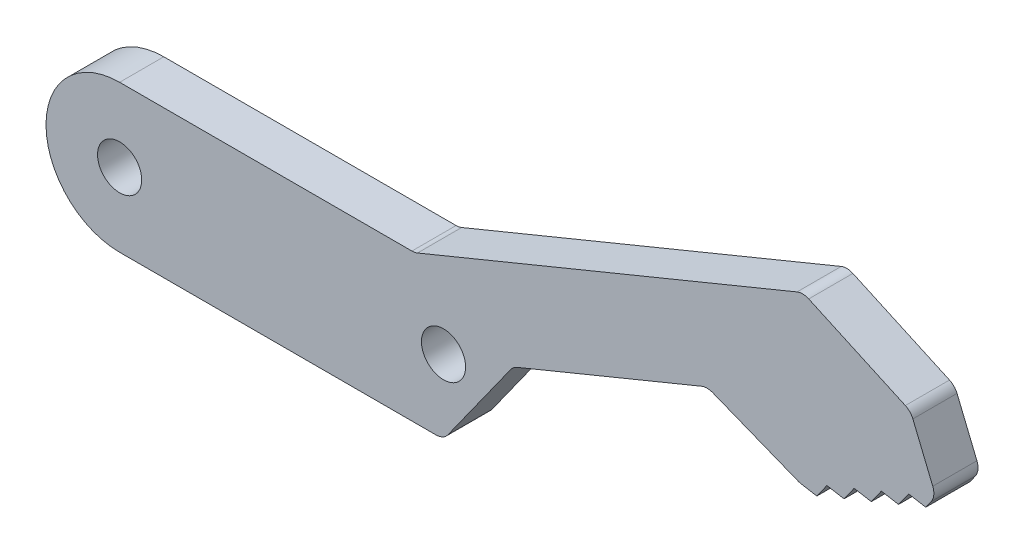
SolidWorks part; units mm, degrees
ref_plane "Front Plane" through (0, 0, 0) normal (0, 0, 1) x (1, 0, 0)
ref_plane "Top Plane" through (0, 0, 0) normal (0, 1, 0) x (1, 0, 0)
ref_plane "Right Plane" through (0, 0, 0) normal (1, 0, 0) x (0, 0, -1)
sketch "Sketch1" plane through (0, 0, 0) normal (0, 0, 1) x (1, 0, 0)
  line L0 (0, 0) -> (22, 0) construction
  line L7 (0, 5) -> (20.05, 5)
  line L8 (0, -5) -> (22, -5)
  line L9 (20.05, 5) -> (23.9914, -4.5863) construction
  line L10 (20.05, 5) -> (51.4959, 17.929) construction
  line L11 (23.9914, -4.5863) -> (46.1885, 4.54) construction
  line L12 (51.4959, 17.929) -> (55.4373, 8.3426) construction
  line L13 (20.05, 5) -> (46.409, 15.8375)
  line L14 (46.409, 15.8375) -> (53.7261, 12.5046)
  line L15 (53.7261, 12.5046) -> (55.4373, 8.3426)
  line L17 (46.1885, 4.54) -> (39.9002, 7.0361)
  line L18 (39.9002, 7.0361) -> (26.7299, 1.6211)
  line L19 (46.1885, 4.54) -> (47.3529, 4.3376)
  line L20 (47.3529, 4.3376) -> (48.0382, 5.3005)
  line L21 (47.3529, 4.3376) -> (54.752, 7.3797) construction
  line L22 (48.0382, 5.3005) -> (49.2027, 5.0981)
  line L23 (49.2027, 5.0981) -> (49.888, 6.0611)
  line L24 (49.888, 6.0611) -> (51.0524, 5.8587)
  line L25 (51.0524, 5.8587) -> (51.7378, 6.8216)
  line L26 (51.7378, 6.8216) -> (52.9022, 6.6192)
  line L27 (52.9022, 6.6192) -> (53.5875, 7.5821)
  line L28 (53.5875, 7.5821) -> (54.752, 7.3797)
  line L29 (54.752, 7.3797) -> (55.4373, 8.3426)
  line L30 (26.7299, 1.6211) -> (22, -5)
  arc A2 (0, 5) -> (0, -5) centre (0, 0) ccw
  circle A4 centre (0, 0) radius 1.5
  circle A5 centre (22, 0) radius 1.5
  point P3 (11, 0)
  dimension "D11" = 3
  dimension "D1" = 22
  dimension "D2" = 10
  dimension "D3" = 157.65
  dimension "D5" = 34
  dimension "D6" = 14.24
  dimension "D7" = 10
  dimension "D8" = 4.5
  dimension "D9" = 5.5
  dimension "D10" = 136
  dimension "D12" = 2
extrude "Boss-Extrude1" add sketch "Sketch1" along normal mid plane 3
fillet "Fillet1" radius 1 8 edges at (20.05, 5, 0) (46.1885, 4.54, 0) (39.9002, 7.0361, 0) (26.7299, 1.6211, 0) (22, -5, 0) (46.409, 15.8375, 0) (53.7261, 12.5046, 0) (55.4373, 8.3426, 0)
